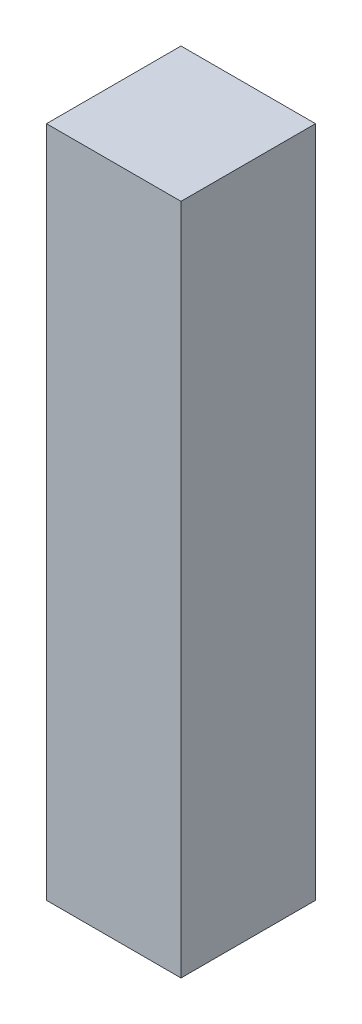
SolidWorks part; units mm, degrees
ref_plane "Front Plane" through (0, 0, 0) normal (0, 0, 1) x (1, 0, 0)
ref_plane "Top Plane" through (0, 0, 0) normal (0, 1, 0) x (1, 0, 0)
ref_plane "Right Plane" through (0, 0, 0) normal (1, 0, 0) x (0, 0, -1)
sketch "Sketch1" plane through (0, 0, 0) normal (0, 1, 0) x (1, 0, 0)
  line L1 (0, 0) -> (100, 0)
  line L2 (0, 0) -> (0, 100)
  line L3 (0, 100) -> (100, 100)
  line L4 (100, 0) -> (100, 100)
  dimension "D1" = 100
  dimension "D2" = 100
extrude "Boss-Extrude1" add sketch "Sketch1" along normal blind 500
